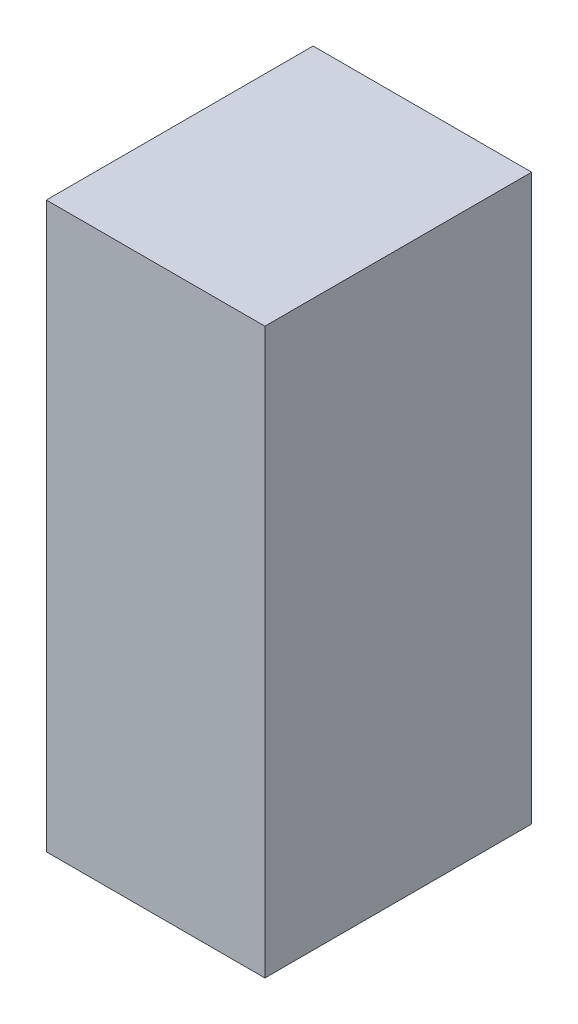
SolidWorks part; units mm, degrees
ref_plane "Plano frontal" through (0, 0, 0) normal (0, 0, 1) x (1, 0, 0)
ref_plane "Plano superior" through (0, 0, 0) normal (0, 1, 0) x (1, 0, 0)
ref_plane "Plano direito" through (0, 0, 0) normal (1, 0, 0) x (0, 0, -1)
sketch "Esboço1" plane through (0, 0, 0) normal (0, 0, 1) x (1, 0, 0)
  line L1 (0, 0) -> (18.023, 0)
  line L2 (0, 0) -> (0, 46.5565)
  line L3 (0, 46.5565) -> (18.023, 46.5565)
  line L4 (18.023, 0) -> (18.023, 46.5565)
extrude "Ressalto-extrusão1" add sketch "Esboço1" along normal blind 22
